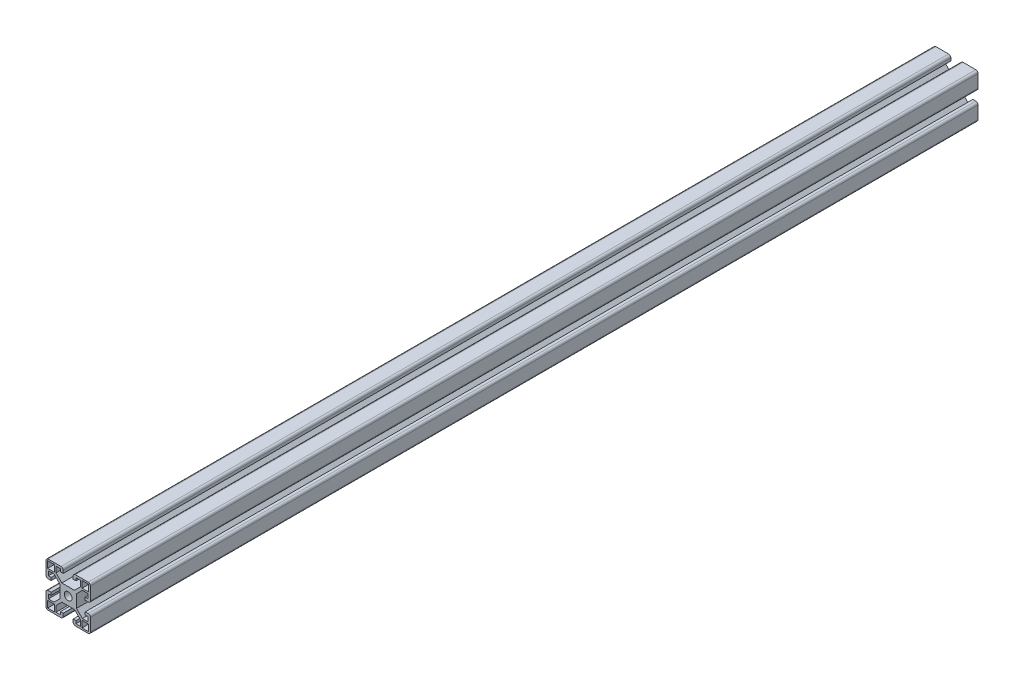
SolidWorks part; units mm, degrees
ref_plane "Alzado" through (0, 0, 0) normal (0, 0, 1) x (1, 0, 0)
ref_plane "Planta" through (0, 0, 0) normal (0, 1, 0) x (1, 0, 0)
ref_plane "Vista lateral" through (0, 0, 0) normal (1, 0, 0) x (0, 0, -1)
sketch "Croquis1" plane through (0, 0, 0) normal (0, 0, 1) x (1, 0, 0)
  line L1 (-20, -20) -> (20, -20)
  line L2 (-20, -20) -> (-20, 20)
  line L3 (-20, 20) -> (20, 20)
  line L4 (20, -20) -> (20, 20)
  line L5 (-20, -20) -> (20, 20) construction
  line L6 (-20, 20) -> (20, -20) construction
  point P0 (0, 0)
  dimension "D1" = 40
  dimension "D2" = 40
extrude "Saliente-Extruir1" add sketch "Croquis1" along normal blind 800
sketch "Croquis2" plane through (0, 0, 800) normal (0, 0, 1) x (1, 0, 0)
  line L0 (-7.5, 7.5) -> (-20, 20) construction
  line L1 (5.7336, -7.5014) -> (-5.7336, -7.5014)
  line L2 (7.5013, -5.7336) -> (7.5013, 5.7336)
  line L3 (5.7336, 7.5014) -> (-5.7336, 7.5014)
  line L4 (-7.5013, -5.7336) -> (-7.5013, 5.7336)
  line L5 (7.5, -7.5) -> (-7.5, 7.5) construction
  line L6 (7.5, 7.5) -> (-7.5, -7.5) construction
  line L7 (-5.7336, 7.5014) -> (-11, 12.7678)
  line L8 (-7.5013, 5.7336) -> (-12.7678, 11)
  line L9 (-20, 20) -> (-20, -20) construction
  line L10 (-18.5, 12.5) -> (-12.5, 12.5)
  line L11 (-18.5, 12.5) -> (-18.5, 18.5)
  line L12 (-18.5, 18.5) -> (-12.5, 18.5)
  line L13 (-12.5, 12.5) -> (-12.5, 18.5)
  line L14 (-18.5, 12.5) -> (-12.5, 18.5) construction
  line L15 (-18.5, 18.5) -> (-12.5, 12.5) construction
  line L16 (-11, 12.7678) -> (-11, 18)
  line L17 (-11, 18) -> (-7, 18)
  line L18 (-7, 18) -> (-7, 15.5)
  line L19 (-7, 15.5) -> (-4.5, 15.5)
  line L20 (-4.5, 15.5) -> (-4.5, 20)
  line L21 (20, 20) -> (-20, 20) construction
  line L22 (0, 20) -> (0, -20) construction
  line L23 (-20, -20) -> (20, -20) construction
  line L24 (-12.7678, 11) -> (-17.8676, 11)
  line L25 (-17.8676, 11) -> (-17.8676, 7)
  line L26 (-17.8676, 7) -> (-15.3676, 7)
  line L27 (-15.3676, 7) -> (-15.3676, 4.5)
  line L28 (-15.3676, 4.5) -> (-20, 4.5)
  line L29 (18.5, 18.5) -> (12.5, 12.5) construction
  line L30 (18.5, 12.5) -> (12.5, 18.5) construction
  line L31 (7.5, 7.5) -> (20, 20) construction
  line L32 (15.3676, 4.5) -> (20, 4.5)
  line L33 (15.3676, 7) -> (15.3676, 4.5)
  line L34 (17.8676, 7) -> (15.3676, 7)
  line L35 (17.8676, 11) -> (17.8676, 7)
  line L36 (12.7678, 11) -> (17.8676, 11)
  line L37 (4.5, 15.5) -> (4.5, 20)
  line L38 (7, 15.5) -> (4.5, 15.5)
  line L39 (7, 18) -> (7, 15.5)
  line L40 (11, 18) -> (7, 18)
  line L41 (11, 12.7678) -> (11, 18)
  line L42 (12.5, 12.5) -> (12.5, 18.5)
  line L43 (18.5, 18.5) -> (12.5, 18.5)
  line L44 (18.5, 12.5) -> (18.5, 18.5)
  line L45 (18.5, 12.5) -> (12.5, 12.5)
  line L46 (7.5013, 5.7336) -> (12.7678, 11)
  line L47 (5.7336, 7.5014) -> (11, 12.7678)
  line L48 (20, 0) -> (-20, 0) construction
  line L49 (20, -20) -> (20, 20) construction
  line L50 (7.5, -7.5) -> (20, -20) construction
  line L51 (18.5, -12.5) -> (12.5, -18.5) construction
  line L52 (18.5, -18.5) -> (12.5, -12.5) construction
  line L53 (-18.5, -18.5) -> (-12.5, -12.5) construction
  line L54 (-18.5, -12.5) -> (-12.5, -18.5) construction
  line L55 (-7.5, -7.5) -> (-20, -20) construction
  line L56 (5.7336, -7.5014) -> (11, -12.7678)
  line L57 (7.5013, -5.7336) -> (12.7678, -11)
  line L58 (18.5, -12.5) -> (12.5, -12.5)
  line L59 (18.5, -12.5) -> (18.5, -18.5)
  line L60 (18.5, -18.5) -> (12.5, -18.5)
  line L61 (12.5, -12.5) -> (12.5, -18.5)
  line L62 (11, -12.7678) -> (11, -18)
  line L63 (11, -18) -> (7, -18)
  line L64 (7, -18) -> (7, -15.5)
  line L65 (7, -15.5) -> (4.5, -15.5)
  line L66 (4.5, -15.5) -> (4.5, -20)
  line L67 (12.7678, -11) -> (17.8676, -11)
  line L68 (17.8676, -11) -> (17.8676, -7)
  line L69 (17.8676, -7) -> (15.3676, -7)
  line L70 (15.3676, -7) -> (15.3676, -4.5)
  line L71 (15.3676, -4.5) -> (20, -4.5)
  line L72 (-15.3676, -4.5) -> (-20, -4.5)
  line L73 (-15.3676, -7) -> (-15.3676, -4.5)
  line L74 (-17.8676, -7) -> (-15.3676, -7)
  line L75 (-17.8676, -11) -> (-17.8676, -7)
  line L76 (-12.7678, -11) -> (-17.8676, -11)
  line L77 (-4.5, -15.5) -> (-4.5, -20)
  line L78 (-7, -15.5) -> (-4.5, -15.5)
  line L79 (-7, -18) -> (-7, -15.5)
  line L80 (-11, -18) -> (-7, -18)
  line L81 (-11, -12.7678) -> (-11, -18)
  line L82 (-12.5, -12.5) -> (-12.5, -18.5)
  line L83 (-18.5, -18.5) -> (-12.5, -18.5)
  line L84 (-18.5, -12.5) -> (-18.5, -18.5)
  line L85 (-18.5, -12.5) -> (-12.5, -12.5)
  line L86 (-7.5013, -5.7336) -> (-12.7678, -11)
  line L87 (-5.7336, -7.5014) -> (-11, -12.7678)
  line L88 (5.7336, -7.5014) -> (-5.7336, -7.5014)
  line L89 (-20, -4.5) -> (-20, 4.5)
  line L90 (20, 4.5) -> (20, -4.5)
  line L91 (-4.5, -20) -> (4.5, -20)
  line L92 (-4.5, 20) -> (4.5, 20)
  circle A0 centre (0, 0) radius 3.5
  point P0 (0, 0)
  point P14 (-15.5, 15.5)
  point P56 (15.5, 15.5)
  point P99 (15.5, -15.5)
  point P100 (-15.5, -15.5)
  line M20 (20, -20) -> (20, 20)
  line M21 (20, 20) -> (-20, 20)
  line M22 (-20, 20) -> (-20, -20)
  line M23 (-20, -20) -> (20, -20)
  dimension "D3" = 7
  dimension "D1" = 15
  dimension "D2" = 15
  dimension "D4" = 1.25
  dimension "D5" = 1.25
  dimension "D6" = 1.5
  dimension "D7" = 6
  dimension "D8" = 6
  dimension "D9" = 1.5
  dimension "D10" = 2
  dimension "D11" = 4
  dimension "D12" = 2.5
  dimension "D13" = 2.5
  dimension "D14" = 1.5
  dimension "D15" = 4
  dimension "D16" = 2.5
  dimension "D17" = 2.5
extrude "Cortar-Extruir2" cut sketch "Croquis2" against normal up to surface (800 mm away) contours L10 L13 L12 L11 | L3 L47 L41 L40 L39 L38 L37 L20 L19 L18 L17 L16 L7 M21 | L45 L44 L43 L42 | L70 L71 L32 L33 L34 L35 L36 L46 L2 L57 L67 L68 L69 M20 | L86 L4 L8 L24 L25 L26 L27 L28 L72 L73 L74 L75 L76 M22 | A0 | L1 L87 L81 L80 L79 L78 L77 L66 L65 L64 L63 L62 L56 M23 | L85 L84 L83 L82 | L58 L61 L60 L59 up to face at (0, 0, 0)
fillet "Redondeo1" radius 2 4 edges at (-20, -20, 400) (-20, 20, 400) (20, -20, 400) (20, 20, 400)
fillet "Redondeo2" radius 2 8 edges at (-20, -4.5, 400) (-20, 4.5, 400) (-4.5, -20, 400) (4.5, -20, 400) (20, 4.5, 400) (20, -4.5, 400) (4.5, 20, 400) (-4.5, 20, 400)
